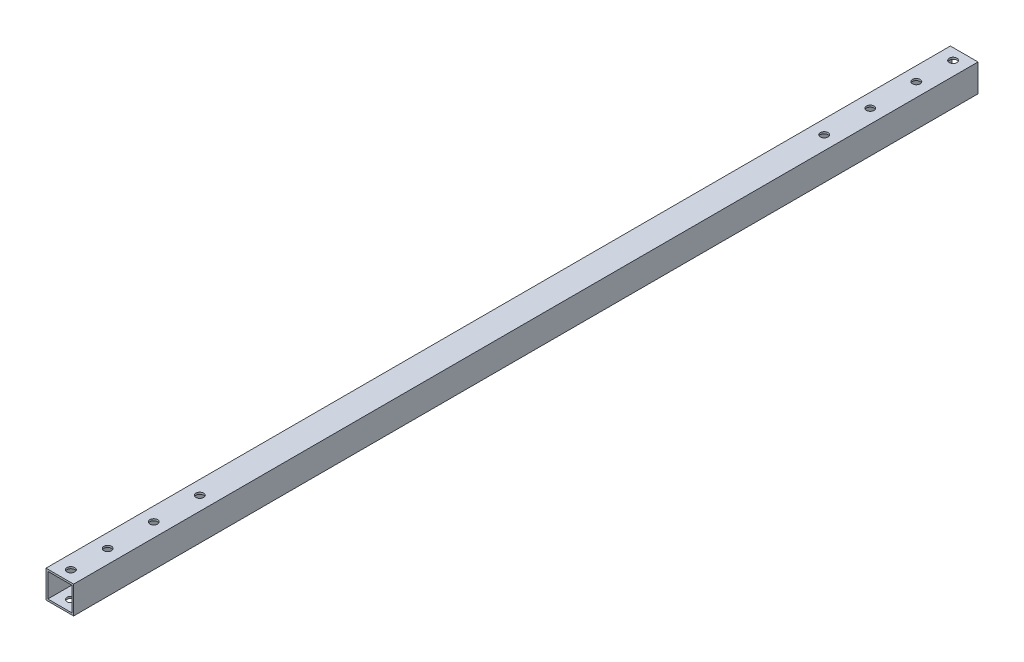
SolidWorks part; units mm, degrees
ref_plane "前视基准面" through (0, 0, 0) normal (0, 0, 1) x (1, 0, 0)
ref_plane "上视基准面" through (0, 0, 0) normal (0, 1, 0) x (1, 0, 0)
ref_plane "右视基准面" through (0, 0, 0) normal (1, 0, 0) x (0, 0, -1)
other "Configuration Table"
sketch "草图1" plane through (0, 0, 0) normal (0, 0, 1) x (1, 0, 0)
  line L0 (-6.5, 6.5) -> (-6.5, -6.5)
  line L1 (-7.5, 7.5) -> (-7.5, -7.5)
  line L2 (-7.5, -7.5) -> (7.5, -7.5)
  line L3 (7.5, -7.5) -> (7.5, 7.5)
  line L4 (7.5, 7.5) -> (-7.5, 7.5)
  line L5 (-6.5, -6.5) -> (6.5, -6.5)
  line L6 (6.5, -6.5) -> (6.5, 6.5)
  line L7 (6.5, 6.5) -> (-6.5, 6.5)
  circle A0 centre (0, 0) radius 7.5 construction
  dimension "D1" = 15
  dimension "D2" = 1
extrude "凸台-拉伸1" add sketch "草图1" along normal blind 491
sketch "草图2" plane through (0, 7.5, 0) normal (0, 1, 0) x (1, 0, 0)
  line L0 (0, 0) -> (0, -491) construction
  line L1 (7.5, -491) -> (-7.5, -491) construction
  line L2 (-7.5, -245.5) -> (7.5, -245.5) construction
  line L3 (-7.5, -491) -> (-7.5, 0) construction
  line L4 (7.5, -491) -> (7.5, 0) construction
  line L5 (7.5, 0) -> (-7.5, 0) construction
  circle A0 centre (0, -6) radius 2.1
  circle A1 centre (0, -26) radius 2.1
  circle A2 centre (0, -51) radius 2.1
  circle A3 centre (0, -76) radius 2.1
  circle A4 centre (0, -415) radius 2.1
  circle A5 centre (0, -440) radius 2.1
  circle A6 centre (0, -465) radius 2.1
  circle A7 centre (0, -485) radius 2.1
  dimension "D1" = 4.2
  dimension "D2" = 20
  dimension "D3" = 25
  dimension "D4" = 25
  dimension "D5" = 6
extrude "切除-拉伸1" cut sketch "草图2" against normal blind 500
